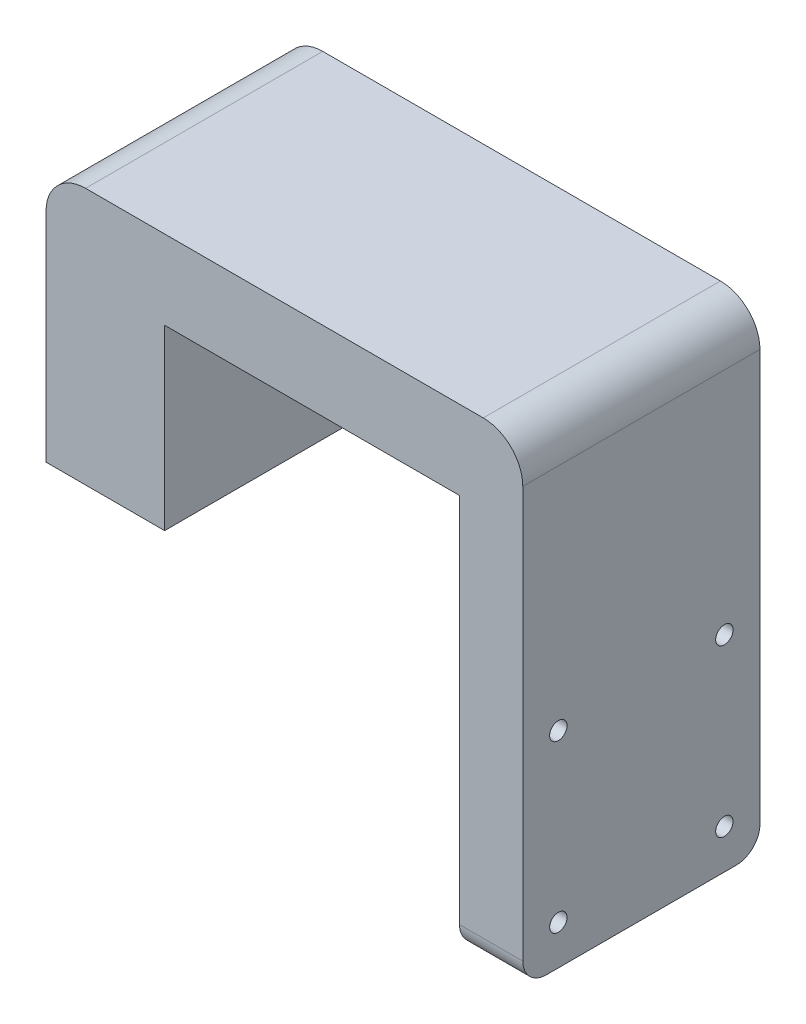
SolidWorks part; units mm, degrees
material "ABS"
ref_plane "正面" through (0, 0, 0) normal (0, 0, 1) x (1, 0, 0)
ref_plane "平面" through (0, 0, 0) normal (0, 1, 0) x (1, 0, 0)
ref_plane "右側面" through (0, 0, 0) normal (1, 0, 0) x (0, 0, -1)
sketch "ｽｹｯﾁ1" plane through (0, 0, 0) normal (0, 0, 1) x (1, 0, 0)
  line L0 (0, 0) -> (-15, 0)
  line L1 (-15, 0) -> (-15, 27.5)
  line L2 (-10, 32.5) -> (40.3, 32.5)
  line L3 (45.3, 27.5) -> (45.3, -27.5)
  line L4 (45.3, -27.5) -> (37.3, -27.5)
  line L5 (0, 0) -> (0, 22.5)
  line L6 (0, 22.5) -> (37.3, 22.5)
  line L7 (37.3, 22.5) -> (37.3, -27.5)
  line L9 (36.845, 7.339) -> (0.845, 7.339)
  line L10 (36.845, 7.339) -> (36.845, -28.661) construction
  line L11 (36.845, -28.661) -> (0.845, -28.661) construction
  line L12 (0.845, 7.339) -> (0.845, -28.661) construction
  arc A0 (40.3, 32.5) -> (45.3, 27.5) centre (40.3, 27.5) cw
  arc A1 (-15, 27.5) -> (-10, 32.5) centre (-10, 27.5) cw
  point P12 (45.3, 32.5)
  dimension "D7" = 5
  dimension "D1" = 37.3
  dimension "D2" = 60
  dimension "D3" = 8
  dimension "D4" = 10
  dimension "D5" = 15
  dimension "D6" = 22.5
  dimension "D8" = 36
extrude "ﾎﾞｽ - 押し出し1" add sketch "ｽｹｯﾁ1" along normal blind 30 contours A1 L1 L0 L5 L6 L7 L4 L3 A0 L2
sketch "ｽｹｯﾁ2" plane through (37.3, 0, 0) normal (-1, 0, 0) x (0, 0, 1)
  line L0 (0, -22.5) -> (30, -22.5) construction
  line L3 (30, -27.5) -> (0, -27.5) construction
  line L4 (30, 22.5) -> (30, -27.5) construction
  circle A0 centre (4.5, -22.5) radius 1.1
  circle A1 centre (25.5, -22.5) radius 1.1
  circle A2 centre (4.5, -1.5) radius 1.1
  circle A3 centre (25.5, -1.5) radius 1.1
  dimension "D1" = 21
  dimension "D3" = 2.2
  dimension "D2" = 4.5
  dimension "D4" = 5
  dimension "D6" = 21
  dimension "D5" = 2
extrude "ｶｯﾄ - 押し出し1" cut sketch "ｽｹｯﾁ2" against normal through all
fillet "ﾌｨﾚｯﾄ1" radius 3 2 edges at (41.3, -27.5, 30) (41.3, -27.5, 0)
sketch "ｽｹｯﾁ3" plane through (37.3, 0, 0) normal (-1, 0, 0) x (0, 0, 1)
  circle A0 centre (4.5, -22.5) radius 3.25
  circle A1 centre (25.5, -22.5) radius 3.25
  circle A2 centre (4.5, -1.5) radius 3.25
  circle A3 centre (25.5, -1.5) radius 3.25
  dimension "D1" = 6.5
extrude "ｶｯﾄ - 押し出し2" cut sketch "ｽｹｯﾁ3" against normal blind 5
